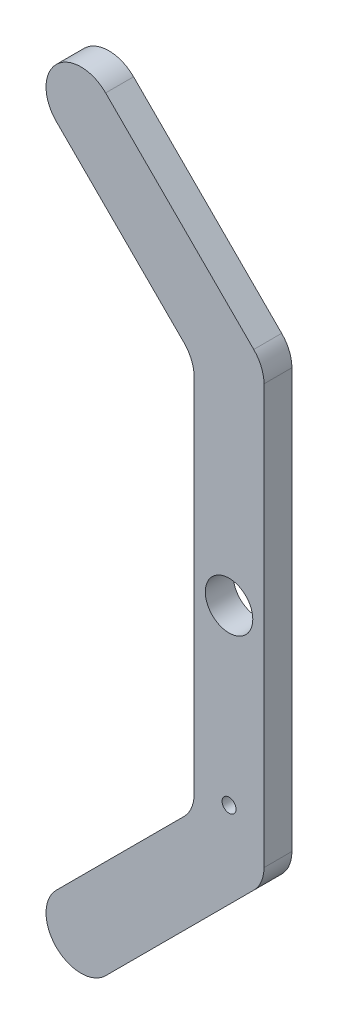
SolidWorks part; units mm, degrees
ref_plane "Front Plane" through (0, 0, 0) normal (0, 0, 1) x (1, 0, 0)
ref_plane "Top Plane" through (0, 0, 0) normal (0, 1, 0) x (1, 0, 0)
ref_plane "Right Plane" through (0, 0, 0) normal (1, 0, 0) x (0, 0, -1)
sketch "Sketch1" plane through (0, 0, 0) normal (0, 0, 1) x (1, 0, 0)
  line L0 (0, -23) -> (0, 7) construction
  line L1 (-2.5, -23) -> (-2.5, 7)
  line L2 (2.5, -23) -> (2.5, 7)
  line L3 (0, -23) -> (-10.6066, -33.6066) construction
  line L4 (1.7678, -24.7678) -> (-8.8388, -35.3744)
  line L5 (-1.7678, -21.2322) -> (-12.3744, -31.8388)
  line L6 (0, 7) -> (-10.6066, 17.6066) construction
  line L7 (-1.7678, 5.2322) -> (-12.3744, 15.8388)
  line L8 (1.7678, 8.7678) -> (-8.8388, 19.3744)
  line L9 (-24.3674, -20.3791) -> (0, -20.3791)
  arc A0 (-2.5, -23) -> (2.5, -23) centre (0, -23) ccw
  arc A1 (2.5, 7) -> (-2.5, 7) centre (0, 7) ccw
  arc A2 (1.7678, -24.7678) -> (-1.7678, -21.2322) centre (0, -23) ccw
  arc A3 (-12.3744, -31.8388) -> (-8.8388, -35.3744) centre (-10.6066, -33.6066) ccw
  arc A4 (-1.7678, 5.2322) -> (1.7678, 8.7678) centre (0, 7) ccw
  arc A5 (-8.8388, 19.3744) -> (-12.3744, 15.8388) centre (-10.6066, 17.6066) ccw
  circle A6 centre (0, -8) radius 1.7
  circle A7 centre (-24.3674, -14.0041) radius 6.375
  circle A8 centre (0, -20.3791) radius 0.5
  point P2 (0, -8)
  point P11 (-5.3033, -28.3033)
  point P18 (-5.3033, 12.3033)
  dimension "D1" = 3.4
  dimension "D4" = 2.5
  dimension "D6" = 12.75
  dimension "D8" = 1
  dimension "D2" = 135
  dimension "D3" = 135
  dimension "D5" = 30
  dimension "D7" = 15
extrude "Boss-Extrude1" add sketch "Sketch1" along normal blind 2
fillet "Fillet1" radius 2.5 2 edges at (-2.5, 5.9645, 1) (-2.5, -21.9645, 1)
